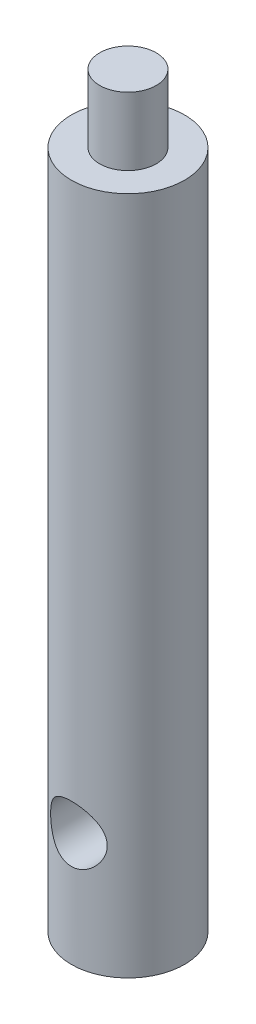
SolidWorks part; units mm, degrees
material "6061 Alloy"
ref_plane "Front Plane" through (0, 0, 0) normal (0, 0, 1) x (1, 0, 0)
ref_plane "Top Plane" through (0, 0, 0) normal (0, 1, 0) x (1, 0, 0)
ref_plane "Right Plane" through (0, 0, 0) normal (1, 0, 0) x (0, 0, -1)
sketch "Sketch1" plane through (0, 0, 0) normal (0, 0, 1) x (1, 0, 0)
  line L0 (0, 66) -> (2.5, 66)
  line L1 (0, -5.5) -> (0, 5.5) construction
  line L2 (2.5, 66) -> (2.5, 60)
  line L3 (2.5, 60) -> (5, 60)
  line L4 (5, 60) -> (5, 0)
  line L5 (5.5, 0) -> (-5.5, 0) construction
  line L7 (5, 0) -> (0, 0)
  line L8 (0, 0) -> (0, 66)
  line L9 (0, 51.1748) -> (0, -51.8924) construction
  dimension "D1" = 2.5
  dimension "D2" = 5
  dimension "D3" = 6
  dimension "D4" = 60
revolve "Revolve1" add sketch "Sketch1" angle 360 about L9
sketch "Sketch2" plane through (0, 0, 0) normal (0, 0, 1) x (1, 0, 0)
  line L0 (0, -5.5) -> (0, 5.5) construction
  line L1 (5.5, 0) -> (-5.5, 0) construction
  circle A0 centre (0, 10) radius 2.5
  dimension "D1" = 5
  dimension "D2" = 10
extrude "Cut-Extrude1" cut sketch "Sketch2" against normal mid plane 20
